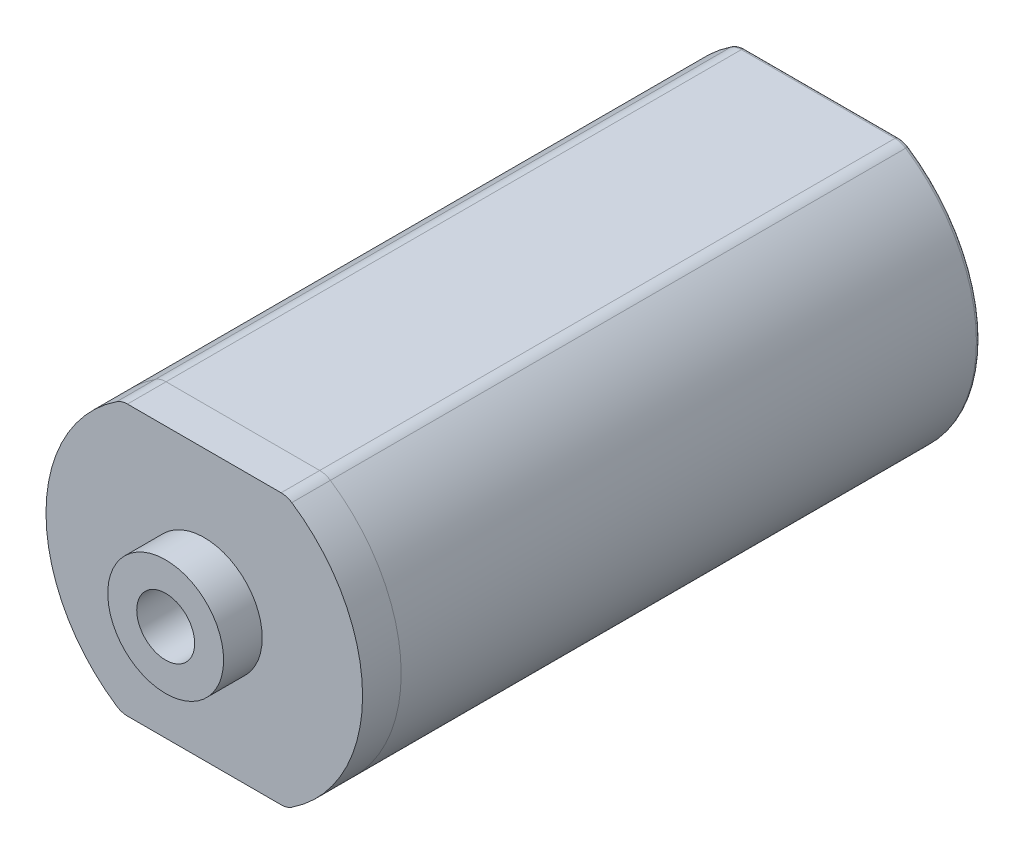
SolidWorks part; units mm, degrees
ref_plane "前视基准面" through (0, 0, 0) normal (0, 0, 1) x (1, 0, 0)
ref_plane "上视基准面" through (0, 0, 0) normal (0, 1, 0) x (1, 0, 0)
ref_plane "右视基准面" through (0, 0, 0) normal (1, 0, 0) x (0, 0, -1)
sketch "草图1" plane through (0, 0, 0) normal (0, 0, 1) x (1, 0, 0)
  circle A0 centre (0, 0) radius 8.2
  dimension "D1" = 16.4
extrude "凸台-拉伸1" add sketch "草图1" along normal blind 30
sketch "草图2" plane through (0, 0, 30) normal (0, 0, 1) x (1, 0, 0)
  line L0 (0, 0) -> (13.1822, 0) construction
  line L1 (-9.1053, 11.077) -> (10.7361, 11.077)
  line L2 (-9.1053, 11.077) -> (-9.1053, 7)
  line L3 (-9.1053, 7) -> (10.7361, 7)
  line L4 (10.7361, 11.077) -> (10.7361, 7)
  line L5 (-9.1053, -7) -> (10.7361, -7)
  line L6 (10.7361, -11.077) -> (10.7361, -7)
  line L7 (-9.1053, -11.077) -> (10.7361, -11.077)
  line L8 (-9.1053, -11.077) -> (-9.1053, -7)
  dimension "D1" = 14
extrude "切除-拉伸1" cut sketch "草图2" against normal through all
fillet "圆角1" radius 1 4 edges at (-4.2708, -7, 15) (4.2708, -7, 15) (4.2708, 7, 15) (-4.2708, 7, 15)
shell "抽壳1" thickness 0.6
sketch "草图4" plane through (0, 0, 0) normal (0, 0, -1) x (-1, 0, 0)
  circle A0 centre (0, 0) radius 3
  dimension "D1" = 6
extrude "凸台-拉伸2" add sketch "草图4" along normal blind 2
sketch "草图7" plane through (0, 0, 0.6) normal (0, 0, 1) x (1, 0, 0)
  arc A28 (-4.2011, 6.3333) -> (-4.2011, -6.3333) centre (0, 0) ccw
  arc A29 (-4.2011, 6.3333) -> (-4.2011, -6.3333) centre (0, 0) ccw
  arc A31 (4.2011, -6.3333) -> (4.2011, 6.3333) centre (0, 0) ccw
  arc A32 (4.2011, -6.3333) -> (4.2011, 6.3333) centre (0, 0) ccw
  dimension "D1" = 0
  dimension "D2" = 0
extrude "拉伸-薄壁1" add sketch "草图7" along normal blind 25 thin thin type one direction reverse wall 1
sketch "草图8" plane through (0, 0, 30) normal (0, 0, 1) x (1, 0, 0)
  line L4 (-3.9799, -7) -> (3.9799, -7)
  line L5 (3.9799, 7) -> (-3.9799, 7)
  line L6 (-3.9799, -7) -> (3.9799, -7)
  line L7 (3.9799, 7) -> (-3.9799, 7)
  arc A12 (-4.5327, 6.8333) -> (-4.5327, -6.8333) centre (0, 0) ccw
  arc A13 (-4.5327, -6.8333) -> (-3.9799, -7) centre (-3.9799, -6) ccw
  arc A14 (3.9799, -7) -> (4.5327, -6.8333) centre (3.9799, -6) ccw
  arc A15 (4.5327, -6.8333) -> (4.5327, 6.8333) centre (0, 0) ccw
  arc A16 (4.5327, 6.8333) -> (3.9799, 7) centre (3.9799, 6) ccw
  arc A17 (-3.9799, 7) -> (-4.5327, 6.8333) centre (-3.9799, 6) ccw
  arc A18 (-4.5327, 6.8333) -> (-4.5327, -6.8333) centre (0, 0) ccw
  arc A19 (-4.5327, -6.8333) -> (-3.9799, -7) centre (-3.9799, -6) ccw
  arc A20 (3.9799, -7) -> (4.5327, -6.8333) centre (3.9799, -6) ccw
  arc A21 (4.5327, -6.8333) -> (4.5327, 6.8333) centre (0, 0) ccw
  arc A22 (4.5327, 6.8333) -> (3.9799, 7) centre (3.9799, 6) ccw
  arc A23 (-3.9799, 7) -> (-4.5327, 6.8333) centre (-3.9799, 6) ccw
  dimension "D1" = 0
extrude "凸台-拉伸3" add sketch "草图8" along normal blind 2 separate body
sketch "草图9" plane through (0, 0, 32) normal (0, 0, 1) x (1, 0, 0)
  circle A0 centre (0, 0) radius 3
  dimension "D1" = 6
extrude "凸台-拉伸4" add sketch "草图9" along normal blind 2
hole_wizard "Ø3.0 (3) 直径孔1" positions "草图5" profile "草图6" hole size "Ø3.0" standard "GB" end condition through all
sketch "草图5" plane through (0, 0, -2) normal (0, 0, -1) x (-1, 0, 0)
  point P0 (0, 0)
sketch "草图6" plane through (0, 0, -2) normal (1, 0, 0) x (0, 1, 0)
  line L0 (0, 0) -> (0, 36)
  line L1 (0, 36) -> (1.5, 36)
  line L2 (1.5, 36) -> (1.5, 0)
  line L5 (1.5, 0) -> (0, 0)
  line L11 (0, -6.35) -> (0, 107.95) construction
  dimension "通孔孔直径" = 3
  dimension "通孔孔深度" = 36
fillet "圆角2" radius 0.2 8 edges at (-4.2686, 6.9574, 0) (-8.2, 0, 0) (-4.2686, -6.9574, 0) (0, -7, 0) (4.2686, -6.9574, 0) (8.2, 0, 0) (4.2686, 6.9574, 0) (0, 7, 0)
sketch "草图12" plane through (0, 0, -2) normal (0, 0, -1) x (-1, 0, 0)
  line L0 (-6, 0) -> (6, 0) construction
  point P5 (0, 0)
  dimension "D1" = 12
hole_wizard "M2.5 螺纹孔1" positions "草图13" profile "草图14" tap size "M2.5" standard "GB"
sketch "草图13" plane through (0, 0, 0) normal (0, 0, -1) x (-1, 0, 0)
  point P0 (-6, 0)
  point P3 (6, 0)
sketch "草图14" plane through (6, 0, 0) normal (1, 0, 0) x (0, 1, 0)
  line L0 (0, 0) -> (0, 14.6159)
  line L1 (0, 14.6159) -> (1.025, 14)
  line L2 (1.025, 14) -> (1.025, 0)
  line L5 (1.025, 0) -> (0, 0)
  line L10 (0, 14.6159) -> (-1.025, 14) construction
  line L11 (0, -6.35) -> (0, 107.95) construction
  dimension "螺纹孔钻头直径" = 2.05
  dimension "螺纹孔钻头深度" = 14
  dimension "导头角度" = 118
cosmetic thread "孔螺蚊线1" parameters "D1"=0.6, "D2"=2.5
cosmetic thread "孔螺蚊线2" parameters "D1"=0.6, "D2"=2.5
